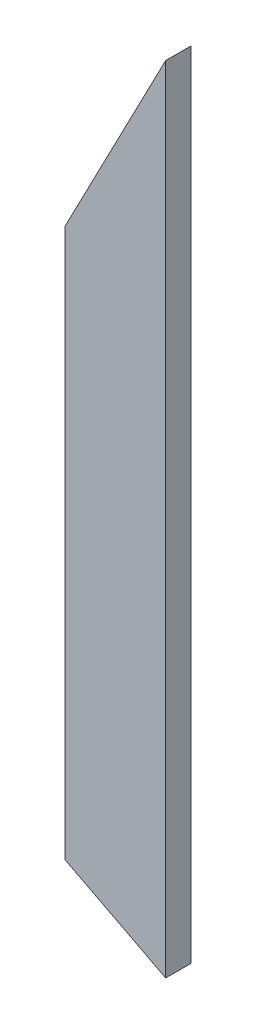
SolidWorks part; units mm, degrees
ref_plane "Front Plane" through (0, 0, 0) normal (0, 0, 1) x (1, 0, 0)
ref_plane "Top Plane" through (0, 0, 0) normal (0, 1, 0) x (1, 0, 0)
ref_plane "Right Plane" through (0, 0, 0) normal (1, 0, 0) x (0, 0, -1)
sketch "Sketch1" plane through (0, 0, 0) normal (0, 0, 1) x (1, 0, 0)
  line L0 (25.4, 200.787) -> (-25.4, 102.9824)
  line L1 (-25.4, 200.787) -> (25.4, 200.787)
  line L2 (-25.4, 200.787) -> (-25.4, -200.787)
  line L3 (-25.4, -200.787) -> (25.4, -200.787)
  line L4 (25.4, 200.787) -> (25.4, -200.787)
  line L5 (-25.4, 200.787) -> (25.4, -200.787) construction
  line L6 (-25.4, -200.787) -> (25.4, 200.787) construction
  line L7 (25.4, -200.787) -> (-25.4, -174.4946)
  point P0 (0, 0)
  dimension "D1" = 401.574
  dimension "D2" = 50.8
  dimension "D3" = 110.2106
  dimension "D4" = 57.2008
extrude "Boss-Extrude1" add sketch "Sketch1" along normal blind 12.7
